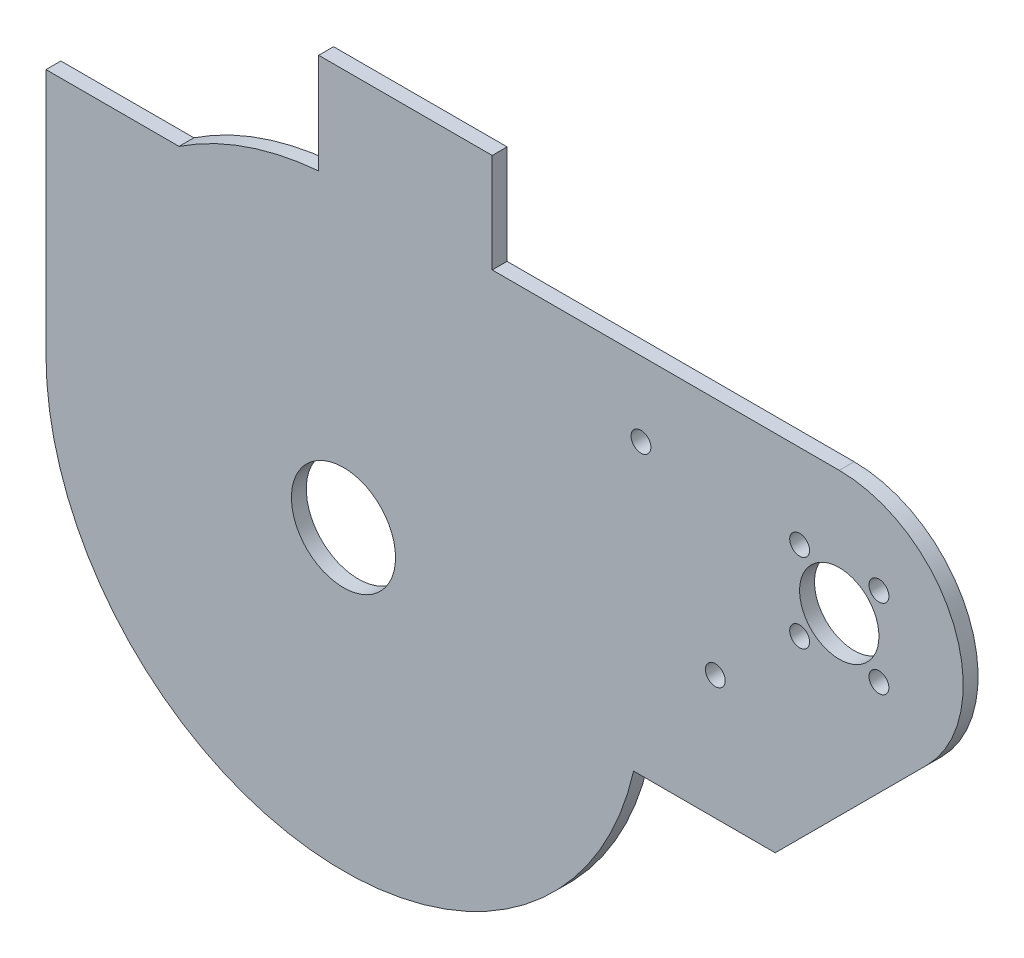
SolidWorks part; units mm, degrees
ref_plane "前视基准面" through (0, 0, 0) normal (0, 0, 1) x (1, 0, 0)
ref_plane "上视基准面" through (0, 0, 0) normal (0, 1, 0) x (1, 0, 0)
ref_plane "右视基准面" through (0, 0, 0) normal (1, 0, 0) x (0, 0, -1)
sketch "Sketch1" plane through (0, 0, 0) normal (0, 0, 1) x (1, 0, 0)
  line L0 (-10.9179, 60) -> (113.3582, 60) construction
  line L3 (-33.1662, 50) -> (-60, 50)
  line L4 (-60, 0) -> (-60, 50)
  line L6 (67.51, -32.8453) -> (81.2655, -19.0899) construction
  line L7 (81.2655, -19.0899) -> (117.6777, 17.3223)
  line L12 (58.5132, -13.2742) -> (87.0811, -13.2742)
  line L13 (0, 60) -> (100, 60)
  arc A0 (0, 60) -> (58.5132, -13.2742) centre (0, 0) ccw
  circle A2 centre (0, 0) radius 10.5
  arc A8 (117.6777, 17.3223) -> (100, 60) centre (100, 35) ccw
  circle A9 centre (100, 35) radius 8
  dimension "D1" = 120
  dimension "D3" = 21
  dimension "D5" = 50
  dimension "D4" = 100
  dimension "D6" = 16
extrude "Boss-Extrude1" add sketch "Sketch1" along normal blind 3
sketch "Sketch2" plane through (0, 0, 3) normal (0, 0, 1) x (1, 0, 0)
  line L1 (-60, 0) -> (-60, 50) construction
  line L2 (0, 60) -> (100, 60) construction
  line L3 (58.5132, -13.2742) -> (87.0811, -13.2742) construction
  circle A1 centre (0, 0) radius 57
  circle A2 centre (60, 45) radius 2
  circle A3 centre (75, 11.7258) radius 2
  circle A6 centre (100, 35) radius 14
  dimension "D1" = 15
  dimension "D4" = 135
  dimension "D5" = 28
  dimension "D2" = 120
  dimension "D3" = 25
extrude "Cut-Extrude1" cut sketch "Sketch2" against normal up to next contours A2 | A3
sketch "Sketch3" plane through (0, 0, 0) normal (0, 0, -1) x (-1, 0, 0)
  line L4 (-30, 0) -> (-30, 80)
  line L5 (-30, 80) -> (5, 80)
  line L6 (5, 80) -> (5, 48)
  line L7 (5, 48) -> (25.3049, 16.1141)
  circle A2 centre (0, 0) radius 10.5
  arc A4 (-30, 0) -> (25.3049, 16.1141) centre (0, 0) ccw
  dimension "D1" = 80
  dimension "D2" = 35
  dimension "D3" = 32
extrude "Boss-Extrude2" add sketch "Sketch3" against normal blind 3
sketch "Sketch4" plane through (0, 0, 0) normal (0, 0, -1) x (-1, 0, 0)
  line L0 (-30, 80) -> (5, 80) construction
  line L1 (5, 80) -> (5, 48) construction
  line L3 (-20, 65.5961) -> (-5, 65.5961)
  line L4 (-20, 65.5961) -> (-20, 63.5961)
  line L5 (-20, 63.5961) -> (-5, 63.5961)
  line L6 (-5, 65.5961) -> (-5, 63.5961)
  line L7 (-20, 65.5961) -> (-5, 63.5961) construction
  line L8 (-20, 63.5961) -> (-5, 65.5961) construction
  line L9 (-13.5, 72.0961) -> (-11.5, 72.0961)
  line L10 (-13.5, 72.0961) -> (-13.5, 57.0961)
  line L11 (-13.5, 57.0961) -> (-11.5, 57.0961)
  line L12 (-11.5, 72.0961) -> (-11.5, 57.0961)
  line L13 (-13.5, 72.0961) -> (-11.5, 57.0961) construction
  line L14 (-13.5, 57.0961) -> (-11.5, 72.0961) construction
  point P5 (-12.5, 64.5961)
  point P10 (-12.5, 80)
  point P11 (-12.5, 64.5961)
  dimension "D1" = 15
  dimension "D2" = 2
  dimension "D3" = 0
  dimension "D4" = 15
  dimension "D5" = 2
extrude "Boss-Extrude3" add sketch "Sketch4" along normal blind 1 contours L12 L9 L10 L3 | L10 L3 L4 L5 | L12 L3 L10 L5 | L3 L12 L5 L6 | L12 L5 L10 L11
sketch "Sketch5" plane through (0, 0, 3) normal (0, 0, 1) x (1, 0, 0)
  line L0 (100, 48.4826) -> (100, 24.1919) construction
  line L1 (89.5844, 35) -> (110.5191, 35) construction
  circle A0 centre (92, 43) radius 2
  circle A1 centre (108, 43) radius 2
  circle A2 centre (108, 27) radius 2
  circle A3 centre (92, 27) radius 2
  dimension "D1" = 8
  dimension "D2" = 8
extrude "Cut-Extrude2" cut sketch "Sketch5" against normal blind 10
